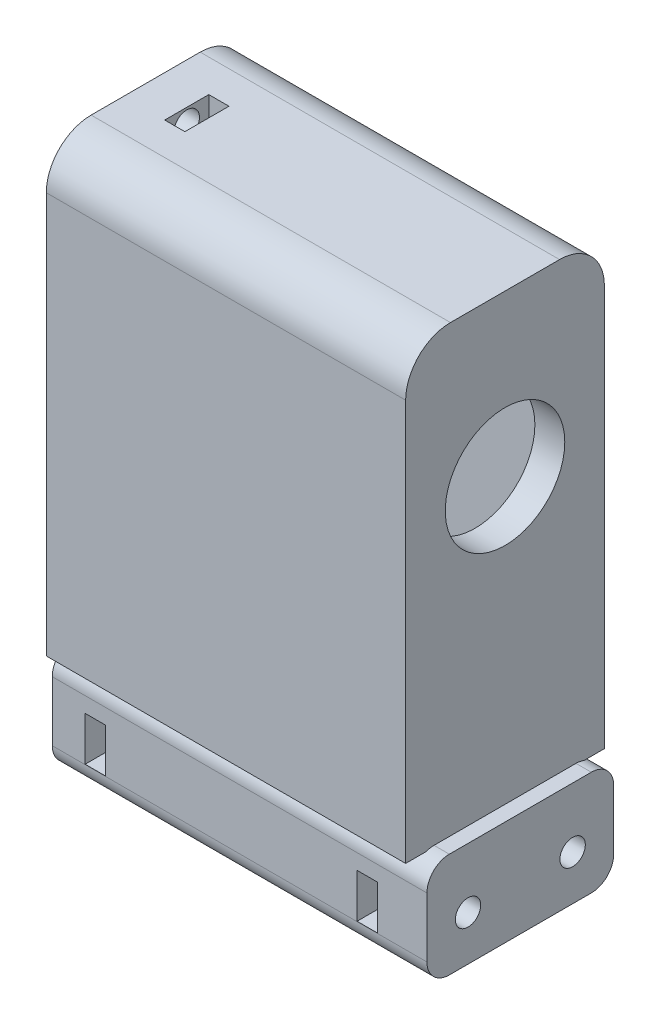
SolidWorks part; units mm, degrees
ref_plane "Front Plane" through (0, 0, 0) normal (0, 0, 1) x (1, 0, 0)
ref_plane "Top Plane" through (0, 0, 0) normal (0, 1, 0) x (1, 0, 0)
ref_plane "Right Plane" through (0, 0, 0) normal (1, 0, 0) x (0, 0, -1)
sketch "Sketch1" plane through (0, 0, 0) normal (1, 0, 0) x (0, 0, -1)
  line L0 (-1.5, 271.5) -> (-1.5, 279.5)
  line L1 (-4.5, 282.5) -> (-23.5, 282.5)
  line L2 (-26.5, 279.5) -> (-26.5, 271.5)
  line L3 (-23.5, 268.5) -> (-4.5, 268.5)
  arc A0 (-4.5, 268.5) -> (-1.5, 271.5) centre (-4.5, 271.5) ccw
  arc A1 (-1.5, 279.5) -> (-4.5, 282.5) centre (-4.5, 279.5) ccw
  arc A2 (-23.5, 282.5) -> (-26.5, 279.5) centre (-23.5, 279.5) ccw
  arc A3 (-26.5, 271.5) -> (-23.5, 268.5) centre (-23.5, 271.5) ccw
extrude "Tail block" add sketch "Sketch1" along normal blind 50.15 from offset 21.9
sketch "Sketch2" plane through (0, 0, 0) normal (1, 0, 0) x (0, 0, -1)
  line L0 (-0.7, 282.3) -> (-0.7, 336)
  line L1 (-6.7, 342) -> (-21.3, 342)
  line L2 (-27.3, 336) -> (-27.3, 282.3)
  line L3 (-27.3, 282.3) -> (-0.7, 282.3)
  arc A0 (-0.7, 336) -> (-6.7, 342) centre (-6.7, 336) ccw
  arc A1 (-21.3, 342) -> (-27.3, 336) centre (-21.3, 336) ccw
  circle A2 centre (-14, 320.5) radius 8
extrude "Nose wall +X" add sketch "Sketch2" along normal blind 4 from offset 22.2
sketch "Sketch3" plane through (0, 0, 0) normal (1, 0, 0) x (0, 0, -1)
  line L0 (-0.7, 282.3) -> (-0.7, 336)
  line L1 (-6.7, 342) -> (-21.3, 342)
  line L2 (-27.3, 336) -> (-27.3, 282.3)
  line L3 (-27.3, 282.3) -> (-24.3, 282.3)
  line L4 (-24.3, 282.3) -> (-24.3, 337)
  line L5 (-23.3, 338) -> (-4.7, 338)
  line L6 (-3.7, 337) -> (-3.7, 282.3)
  line L7 (-3.7, 282.3) -> (-0.7, 282.3)
  arc A0 (-0.7, 336) -> (-6.7, 342) centre (-6.7, 336) ccw
  arc A1 (-21.3, 342) -> (-27.3, 336) centre (-21.3, 336) ccw
  arc A2 (-24.3, 337) -> (-23.3, 338) centre (-23.3, 337) cw
  arc A3 (-4.7, 338) -> (-3.7, 337) centre (-4.7, 337) cw
extrude "Nose walls" add sketch "Sketch3" along normal blind 44.3 from offset 21.9
sketch "Sketch4" plane through (0, 0, 0) normal (1, 0, 0) x (0, 0, -1)
  line L0 (-3.5, 330.9) -> (-3.5, 338.9)
  line L1 (-3.5, 338.9) -> (-24.5, 338.9)
  line L2 (-24.5, 338.9) -> (-24.5, 330.9)
  line L3 (-24.5, 330.9) -> (-3.5, 330.9)
  line L4 (-3.5, 281.4) -> (-3.5, 289.4)
  line L5 (-3.5, 289.4) -> (-24.5, 289.4)
  line L6 (-24.5, 289.4) -> (-24.5, 281.4)
  line L7 (-24.5, 281.4) -> (-3.5, 281.4)
extrude "Head servo ledges" add sketch "Sketch4" along normal blind 14.2 from offset 8.2
sketch "Sketch5" plane through (0, 0, 0) normal (1, 0, 0) x (0, 0, -1)
  circle A0 centre (-9, 334.9) radius 1.7
  circle A1 centre (-19, 334.9) radius 1.7
  circle A2 centre (-9, 285.4) radius 1.7
  circle A3 centre (-19, 285.4) radius 1.7
extrude "Tab bolt holes" cut sketch "Sketch5" along normal blind 9.2 from offset 8
sketch "Sketch6" plane through (0, 0, 0) normal (1, 0, 0) x (0, 0, -1)
  line L0 (-6.05, 333.1968) -> (-6.05, 336.6032)
  line L1 (-6.05, 336.6032) -> (-9, 338.3064)
  line L2 (-9, 338.3064) -> (-11.95, 336.6032)
  line L3 (-11.95, 336.6032) -> (-11.95, 333.1968)
  line L4 (-11.95, 333.1968) -> (-11.95, 330.4)
  line L5 (-11.95, 330.4) -> (-6.05, 330.4)
  line L6 (-6.05, 330.4) -> (-6.05, 333.1968)
  line L7 (-16.05, 333.1968) -> (-16.05, 336.6032)
  line L8 (-16.05, 336.6032) -> (-19, 338.3064)
  line L9 (-19, 338.3064) -> (-21.95, 336.6032)
  line L10 (-21.95, 336.6032) -> (-21.95, 333.1968)
  line L11 (-21.95, 333.1968) -> (-21.95, 330.4)
  line L12 (-21.95, 330.4) -> (-16.05, 330.4)
  line L13 (-16.05, 330.4) -> (-16.05, 333.1968)
  line L14 (-11.95, 287.1032) -> (-11.95, 283.6968)
  line L15 (-11.95, 283.6968) -> (-9, 281.9936)
  line L16 (-9, 281.9936) -> (-6.05, 283.6968)
  line L17 (-6.05, 283.6968) -> (-6.05, 287.1032)
  line L18 (-6.05, 287.1032) -> (-6.05, 289.9)
  line L19 (-6.05, 289.9) -> (-11.95, 289.9)
  line L20 (-11.95, 289.9) -> (-11.95, 287.1032)
  line L21 (-21.95, 287.1032) -> (-21.95, 283.6968)
  line L22 (-21.95, 283.6968) -> (-19, 281.9936)
  line L23 (-19, 281.9936) -> (-16.05, 283.6968)
  line L24 (-16.05, 283.6968) -> (-16.05, 287.1032)
  line L25 (-16.05, 287.1032) -> (-16.05, 289.9)
  line L26 (-16.05, 289.9) -> (-21.95, 289.9)
  line L27 (-21.95, 289.9) -> (-21.95, 287.1032)
extrude "Tab nut slots" cut sketch "Sketch6" along normal blind 2.7 from offset 11.7
sketch "Sketch7" plane through (0, 0, 0) normal (1, 0, 0) x (0, 0, -1)
  circle A0 centre (-7, 274.5) radius 1.7
  circle A1 centre (-21, 274.5) radius 1.7
extrude "Mount bolt holes" cut sketch "Sketch7" along normal blind 50.55 from offset 22.1
sketch "Sketch8" plane through (0, 0, 0) normal (1, 0, 0) x (0, 0, -1)
  circle A0 centre (-14, 340) radius 1.7
extrude "Cover bolt hole" cut sketch "Sketch8" along normal blind 14.1 from offset 22.1
sketch "Sketch9" plane through (0, 0, 0) normal (1, 0, 0) x (0, 0, -1)
  line L0 (-5.2968, 277.45) -> (-8.7032, 277.45)
  line L1 (-8.7032, 277.45) -> (-10.4064, 274.5)
  line L2 (-10.4064, 274.5) -> (-8.7032, 271.55)
  line L3 (-8.7032, 271.55) -> (-5.2968, 271.55)
  line L4 (-5.2968, 271.55) -> (-1, 271.55)
  line L5 (-1, 271.55) -> (-1, 277.45)
  line L6 (-1, 277.45) -> (-5.2968, 277.45)
  line L7 (-22.7032, 271.55) -> (-19.2968, 271.55)
  line L8 (-19.2968, 271.55) -> (-17.5936, 274.5)
  line L9 (-17.5936, 274.5) -> (-19.2968, 277.45)
  line L10 (-19.2968, 277.45) -> (-22.7032, 277.45)
  line L11 (-22.7032, 277.45) -> (-27, 277.45)
  line L12 (-27, 277.45) -> (-27, 271.55)
  line L13 (-27, 271.55) -> (-22.7032, 271.55)
extrude "D-side nut slots" cut sketch "Sketch9" along normal blind 2.7 from offset 18.9
sketch "Sketch10" plane through (0, 0, 0) normal (1, 0, 0) x (0, 0, -1)
  line L0 (-5.2968, 277.45) -> (-8.7032, 277.45)
  line L1 (-8.7032, 277.45) -> (-10.4064, 274.5)
  line L2 (-10.4064, 274.5) -> (-8.7032, 271.55)
  line L3 (-8.7032, 271.55) -> (-5.2968, 271.55)
  line L4 (-5.2968, 271.55) -> (-1, 271.55)
  line L5 (-1, 271.55) -> (-1, 277.45)
  line L6 (-1, 277.45) -> (-5.2968, 277.45)
  line L7 (-22.7032, 271.55) -> (-19.2968, 271.55)
  line L8 (-19.2968, 271.55) -> (-17.5936, 274.5)
  line L9 (-17.5936, 274.5) -> (-19.2968, 277.45)
  line L10 (-19.2968, 277.45) -> (-22.7032, 277.45)
  line L11 (-22.7032, 277.45) -> (-27, 277.45)
  line L12 (-27, 277.45) -> (-27, 271.55)
  line L13 (-27, 271.55) -> (-22.7032, 271.55)
extrude "I-side nut slots" cut sketch "Sketch10" along normal blind 2.7 from offset 17.5
sketch "Sketch11" plane through (0, 0, 0) normal (1, 0, 0) x (0, 0, -1)
  line L0 (-16.95, 341.7032) -> (-16.95, 338.2968)
  line L1 (-16.95, 338.2968) -> (-14, 336.5936)
  line L2 (-14, 336.5936) -> (-11.05, 338.2968)
  line L3 (-11.05, 338.2968) -> (-11.05, 341.7032)
  line L4 (-11.05, 341.7032) -> (-11.05, 342.5)
  line L5 (-11.05, 342.5) -> (-16.95, 342.5)
  line L6 (-16.95, 342.5) -> (-16.95, 341.7032)
extrude "Cover nut slot" cut sketch "Sketch11" along normal blind 2.7 from offset 16.4
sketch "Sketch12" plane through (0, 0, 0) normal (1, 0, 0) x (0, 0, -1)
  line L0 (-10, 268.2) -> (-10, 282.8)
  line L1 (-10, 282.8) -> (-18, 282.8)
  line L2 (-18, 282.8) -> (-18, 268.2)
  line L3 (-18, 268.2) -> (-10, 268.2)
extrude "Lead channel" cut sketch "Sketch12" along normal blind 14.1 from offset 22.1
